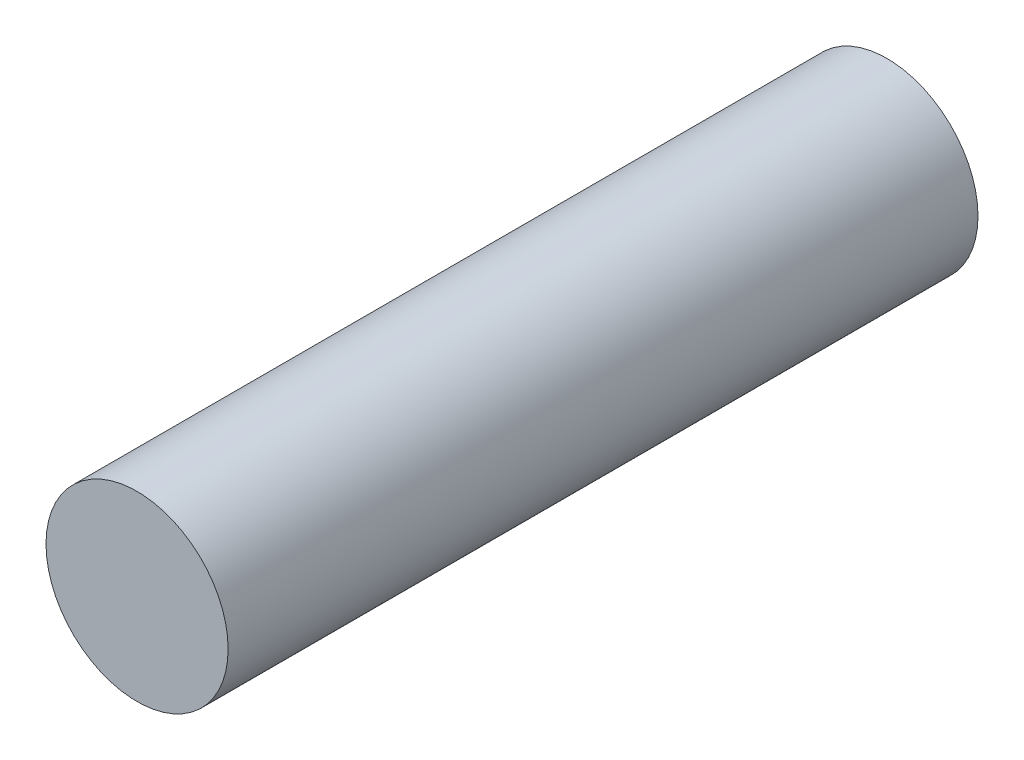
SolidWorks part; units mm, degrees
material "ASTM A36 Steel"
ref_plane "Front Plane" through (0, 0, 0) normal (0, 0, 1) x (1, 0, 0)
ref_plane "Top Plane" through (0, 0, 0) normal (0, 1, 0) x (1, 0, 0)
ref_plane "Right Plane" through (0, 0, 0) normal (1, 0, 0) x (0, 0, -1)
sketch "Sketch1" plane through (0, 0, 0) normal (0, 0, 1) x (1, 0, 0)
  circle A0 centre (0, 0) radius 4.25
  dimension "D1" = 8.5
extrude "Boss-Extrude1" add sketch "Sketch1" along normal blind 35
